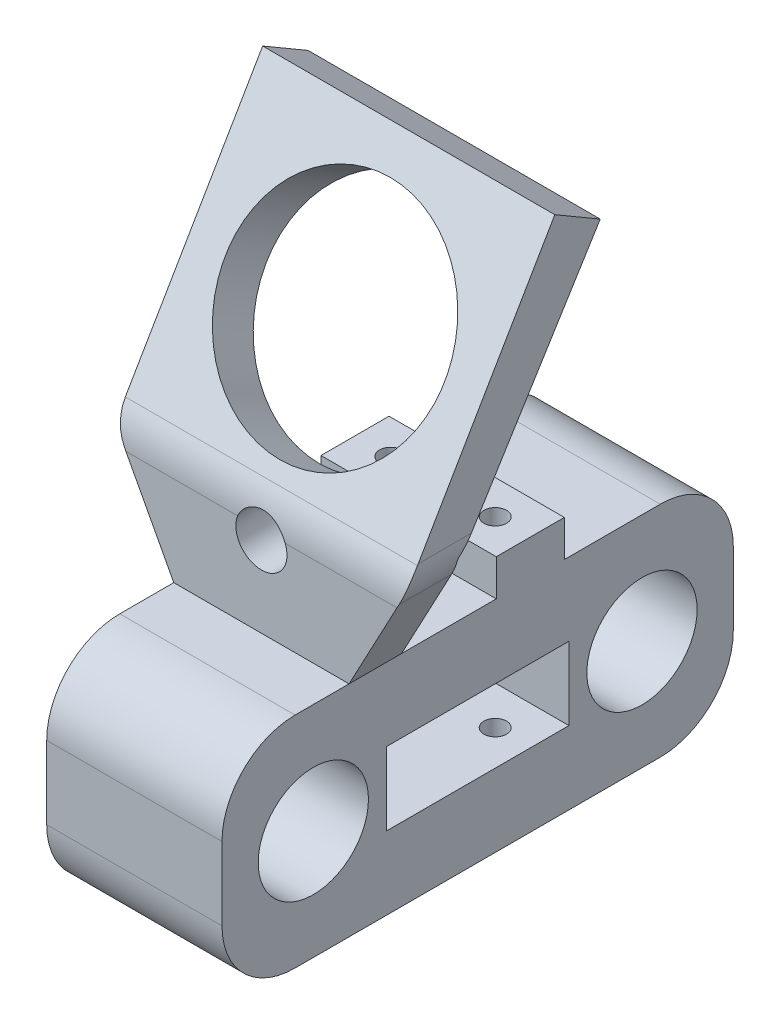
SolidWorks part; units mm, degrees
ref_plane "前视基准面" through (0, 0, 0) normal (0, 0, 1) x (1, 0, 0)
ref_plane "上视基准面" through (0, 0, 0) normal (0, 1, 0) x (1, 0, 0)
ref_plane "右视基准面" through (0, 0, 0) normal (1, 0, 0) x (0, 0, -1)
sketch "草图1" plane through (0, 0, 0) normal (0, 1, 0) x (1, 0, 0)
  line L1 (8.2419, 10.5227) -> (32.2419, 10.5227)
  line L2 (8.2419, 10.5227) -> (8.2419, -59.4773)
  line L3 (8.2419, -59.4773) -> (32.2419, -59.4773)
  line L4 (32.2419, 10.5227) -> (32.2419, -59.4773)
  line L5 (8.2419, 10.5227) -> (32.2419, -59.4773) construction
  line L6 (8.2419, -59.4773) -> (32.2419, 10.5227) construction
  point P4 (20.2419, -24.4773)
  dimension "D1" = 24
  dimension "D2" = 70
extrude "凸台-拉伸1" add sketch "草图1" along normal blind 30
sketch "草图2" plane through (32.2419, 0, 0) normal (1, 0, 0) x (0, 0, -1)
  line L0 (-24.4773, 0) -> (-24.4773, 30) construction
  line L1 (-59.4773, 0) -> (10.5227, 0) construction
  line L2 (-59.4773, 30) -> (10.5227, 30) construction
  line L3 (-59.4773, 15) -> (10.5227, 15) construction
  line L4 (-59.4773, 30) -> (-59.4773, 0) construction
  line L5 (10.5227, 30) -> (10.5227, 0) construction
  circle A0 centre (-46.9773, 15) radius 7.55
  circle A1 centre (-1.9773, 15) radius 7.55
  dimension "D1" = 15.1
  dimension "D3" = 12.5
  dimension "D2" = 45
extrude "切除-拉伸1" cut sketch "草图2" against normal through all
sketch "草图3" plane through (32.2419, 0, 0) normal (1, 0, 0) x (0, 0, -1)
  line L1 (-36.9773, 20) -> (-11.9773, 20)
  line L2 (-36.9773, 20) -> (-36.9773, 10)
  line L3 (-36.9773, 10) -> (-11.9773, 10)
  line L4 (-11.9773, 20) -> (-11.9773, 10)
  line L5 (-36.9773, 20) -> (-11.9773, 10) construction
  line L6 (-36.9773, 10) -> (-11.9773, 20) construction
  point P4 (-24.4773, 15)
extrude "切除-拉伸2" cut sketch "草图3" against normal through all
sketch "草图4" plane through (0, 30, 0) normal (0, 1, 0) x (1, 0, 0)
  line L0 (8.2419, -12.6108) -> (8.2419, -21.9283)
  line L1 (8.2419, 10.5227) -> (8.2419, -59.4773) construction
  line L2 (8.2419, -21.9283) -> (32.2419, -21.9283)
  line L3 (32.2419, -59.4773) -> (32.2419, 10.5227) construction
  line L4 (32.2419, -21.9283) -> (32.2419, -12.6108)
  line L5 (32.2419, -12.6108) -> (8.2419, -12.6108)
extrude "凸台-拉伸2" add sketch "草图4" along normal blind 5
sketch "草图5" plane through (0, 35, 0) normal (0, 1, 0) x (1, 0, 0)
  line L0 (32.2419, -17.2696) -> (8.2419, -17.2696) construction
  line L2 (32.2419, -21.9283) -> (32.2419, -12.6108) construction
  line L3 (8.2419, -12.6108) -> (8.2419, -21.9283) construction
  circle A0 centre (27.4412, -17.2696) radius 1.55
  circle A1 centre (13.1412, -17.2696) radius 1.55
  dimension "D1" = 3.1
  dimension "D2" = 3.1
  dimension "D3" = 14.3
extrude "切除-拉伸3" cut sketch "草图5" against normal blind 31
fillet "圆角1" radius 10 4 edges at (20.2419, 0, 59.4773) (20.2419, 30, 59.4773) (20.2419, 0, -10.5227) (20.2419, 30, -10.5227)
sketch "草图6" plane through (0, 30, 0) normal (0, 1, 0) x (1, 0, 0)
  line L0 (32.2419, -49.4773) -> (32.2419, -21.9283) construction
  line L1 (32.2419, -42.0808) -> (8.2419, -42.0808)
  line L2 (32.2419, -42.0808) -> (32.2419, -34.8822)
  line L3 (32.2419, -34.8822) -> (8.2419, -34.8822)
  line L4 (8.2419, -42.0808) -> (8.2419, -34.8822)
  line L5 (32.2419, -42.0808) -> (8.2419, -34.8822) construction
  line L6 (32.2419, -34.8822) -> (8.2419, -42.0808) construction
  line L7 (8.2419, -21.9283) -> (8.2419, -49.4773) construction
  point P4 (20.2419, -38.4815)
extrude "凸台-拉伸3" add sketch "草图6" along normal blind 15
sketch "草图7" plane through (8.2419, 0, 0) normal (-1, 0, 0) x (0, 0, 1)
  line L1 (42.0808, 45) -> (21.9126, 79.5433)
  line L2 (21.9126, 79.5433) -> (15.6948, 75.9131)
  line L3 (15.6948, 75.9131) -> (34.8822, 45)
  line L4 (34.8822, 45) -> (42.0808, 45)
  dimension "D1" = 7.2
  dimension "D2" = 40
extrude "凸台-拉伸4" add sketch "草图7" against normal up to surface (24 mm away) up to face at (32.2419, 15, 24.4773)
sketch "草图8" plane through (8.2419, 0, 0) normal (-1, 0, 0) x (0, 0, 1)
  line L0 (42.0808, 45) -> (34.8822, 45)
  line L1 (34.8822, 45) -> (15.6948, 75.9131)
  line L2 (15.6948, 75.9131) -> (21.9126, 79.5433)
  line L3 (21.9126, 79.5433) -> (42.0808, 45)
extrude "凸台-拉伸5" add sketch "草图8" along normal blind 8
sketch "草图9" plane through (32.2419, 0, 0) normal (1, 0, 0) x (0, 0, -1)
  line L1 (-42.0808, 45) -> (-34.8822, 45)
  line L2 (-34.8822, 45) -> (-15.6948, 75.9131)
  line L3 (-15.6948, 75.9131) -> (-21.9126, 79.5433)
  line L4 (-21.9126, 79.5433) -> (-42.0808, 45)
extrude "凸台-拉伸6" add sketch "草图9" along normal blind 8
sketch "草图10" plane through (0, 29.7631, 50.977) normal (0, 0.5042, 0.8636) x (1, 0, 0)
  line L0 (40.2419, 37.6439) -> (0.2419, 37.6439) construction
  line L1 (40.2419, 57.6439) -> (40.2419, 17.6439) construction
  line L2 (0.2419, 17.6439) -> (0.2419, 57.6439) construction
  circle A0 centre (20.2419, 37.6439) radius 15
  dimension "D1" = 30
extrude "切除-拉伸4" cut sketch "草图10" against normal blind 16
ref_plane "基准面1" through (0.2419, 45, 42.0808) normal (1, 0, 0) x (0, 0, -1)
sketch "草图12" plane through (0, 0, 42.0808) normal (0, 0, 1) x (1, 0, 0)
  line L1 (0.2419, 45) -> (8.2419, 45)
  line L2 (8.2419, 45) -> (8.2419, 30)
  line L3 (8.2419, 30) -> (0.2419, 45)
extrude "凸台-拉伸7" add sketch "草图12" against normal up to surface (7.1986 mm away) up to face at (20.2419, 37.5, 34.8822)
sketch "草图13" plane through (0, 0, 42.0808) normal (0, 0, 1) x (1, 0, 0)
  line L1 (40.2419, 45) -> (32.2419, 45)
  line L2 (32.2419, 45) -> (32.2419, 30)
  line L3 (32.2419, 30) -> (40.2419, 45)
extrude "凸台-拉伸8" add sketch "草图13" against normal up to surface (7.1986 mm away) up to face at (18.2419, 37.5, 34.8822)
fillet "圆角2" radius 10 1 edges at (20.2419, 45, 42.0808)
fillet "圆角3" radius 10 2 edges at (0.2419, 45, 38.295) (40.2419, 45, 38.295)
sketch "草图14" plane through (0, 0, 42.0808) normal (0, 0, 1) x (1, 0, 0)
  circle A0 centre (20.2415, 41) radius 3.5
  dimension "D1" = 7
extrude "切除-拉伸5" cut sketch "草图14" against normal blind 13
